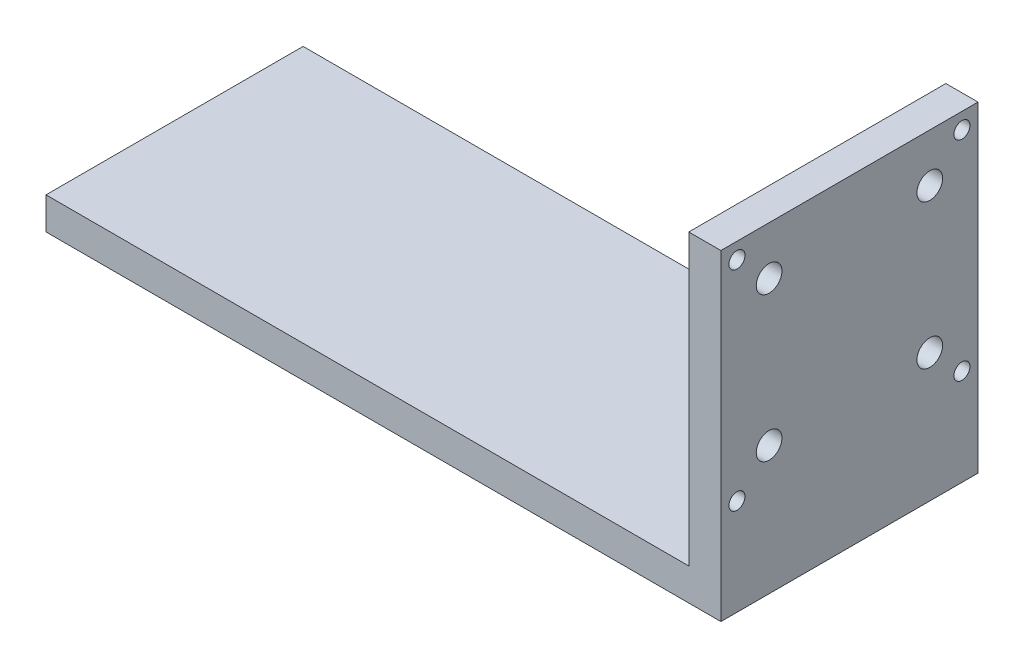
SolidWorks part; units mm, degrees
ref_plane "Front Plane" through (0, 0, 0) normal (0, 0, 1) x (1, 0, 0)
ref_plane "Top Plane" through (0, 0, 0) normal (0, 1, 0) x (1, 0, 0)
ref_plane "Right Plane" through (0, 0, 0) normal (1, 0, 0) x (0, 0, -1)
sketch "Sketch2" plane through (0, 0, 0) normal (0, 1, 0) x (1, 0, 0)
  line L1 (-100, -40) -> (100, -40)
  line L2 (-100, -40) -> (-100, 40)
  line L3 (-100, 40) -> (100, 40)
  line L4 (100, -40) -> (100, 40)
  line L5 (-100, -40) -> (100, 40) construction
  line L6 (-100, 40) -> (100, -40) construction
  point P0 (0, 0)
  dimension "D1" = 200
  dimension "D2" = 80
extrude "Boss-Extrude1" add sketch "Sketch2" along normal blind 10
sketch "Sketch3" plane through (100, 0, 0) normal (1, 0, 0) x (0, 0, -1)
  line L1 (-40, 0) -> (40, 0)
  line L2 (-40, 0) -> (-40, 100)
  line L3 (-40, 100) -> (40, 100)
  line L4 (40, 0) -> (40, 100)
  dimension "D1" = 100
extrude "Boss-Extrude2" add sketch "Sketch3" along normal blind 10
sketch "Sketch6" plane through (100, 0, 0) normal (-1, 0, 0) x (0, 0, 1)
  line L0 (-40, 85) -> (40, 85)
  line L1 (-40, 10) -> (-40, 100) construction
  line L2 (40, 100) -> (40, 10) construction
  line L3 (40, 40) -> (-40, 40)
  line L4 (-40, 100) -> (40, 100) construction
  line L5 (40, 10) -> (-40, 10) construction
  line L6 (-25, 100) -> (-25, 85)
  line L7 (25, 100) -> (25, 85)
  line L8 (-25, 40) -> (-25, 10)
  line L9 (25, 40) -> (25, 10)
  circle A0 centre (-25, 85) radius 4
  circle A1 centre (25, 85) radius 4
  circle A2 centre (-25, 40) radius 4
  circle A3 centre (25, 40) radius 4
  dimension "D5" = 8
  dimension "D1" = 15
  dimension "D2" = 30
  dimension "D3" = 15
  dimension "D4" = 15
extrude "Cut-Extrude2" cut sketch "Sketch6" against normal blind 10 contours A0 | A1 | A2 | A3
sketch "Sketch7" plane through (100, 0, 0) normal (-1, 0, 0) x (0, 0, 1)
  circle A3 centre (-25, 40) radius 4 construction
  circle A7 centre (25, 40) radius 4 construction
  circle A8 centre (25, 40) radius 4
  circle A9 centre (25, 85) radius 4 construction
  circle A10 centre (25, 85) radius 4
  circle A11 centre (-25, 85) radius 4 construction
  circle A12 centre (-25, 85) radius 4
  circle A13 centre (-25, 40) radius 4
  dimension "D4" = 50
sketch "Sketch8" plane through (100, 0, 0) normal (-1, 0, 0) x (0, 0, 1)
  line L0 (-40, 10) -> (-40, 100) construction
  line L1 (40, 100) -> (40, 10) construction
  line L2 (-40, 100) -> (40, 100) construction
  circle A0 centre (-35, 95) radius 2.5
  circle A1 centre (35, 95) radius 2.5
  circle A2 centre (-35, 30) radius 2.5
  circle A3 centre (35, 30) radius 2.5
  dimension "D3" = 5
  dimension "D4" = 5
  dimension "D7" = 5
  dimension "D8" = 5
  dimension "D1" = 5
  dimension "D2" = 5
  dimension "D5" = 5
  dimension "D6" = 5
  dimension "D9" = 65
  dimension "D10" = 65
extrude "Cut-Extrude3" cut sketch "Sketch8" against normal blind 100
